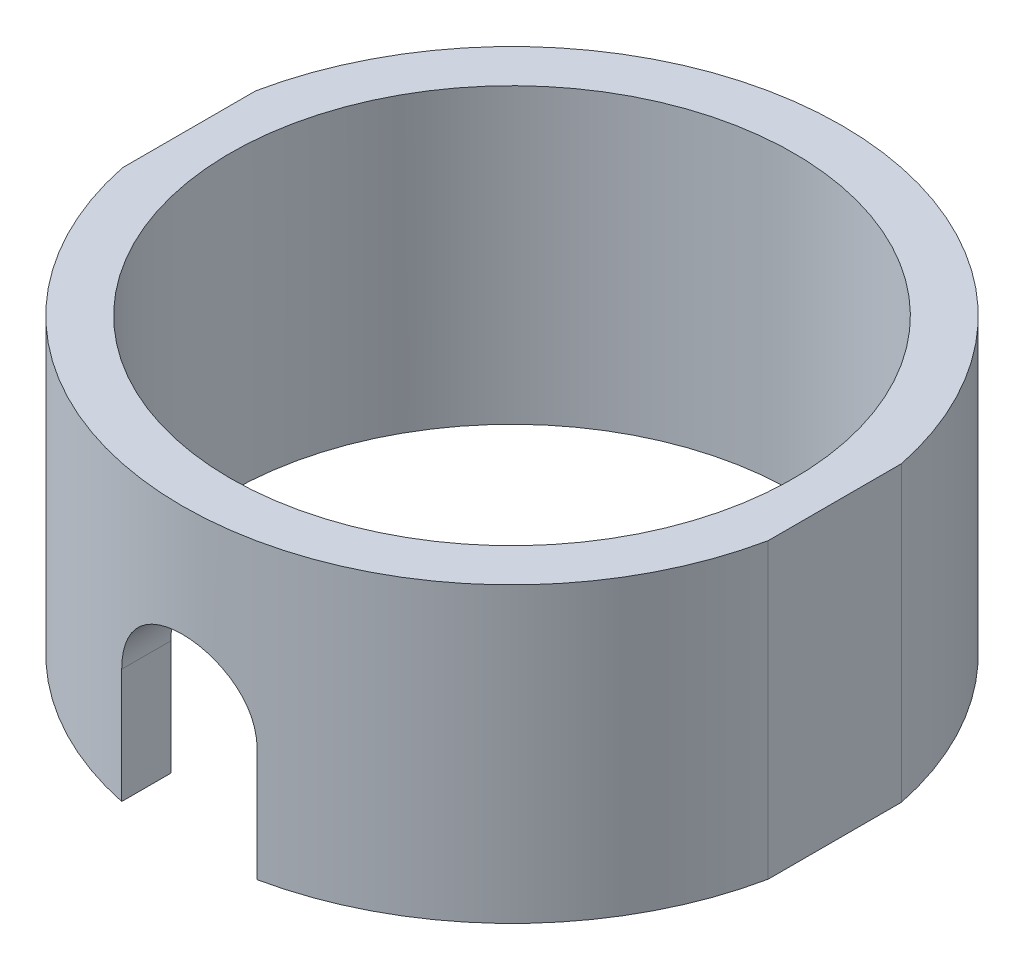
SolidWorks part; units mm, degrees
material "ABS"
ref_plane "Front Plane" through (0, 0, 0) normal (0, 0, 1) x (1, 0, 0)
ref_plane "Top Plane" through (0, 0, 0) normal (0, 1, 0) x (1, 0, 0)
ref_plane "Right Plane" through (0, 0, 0) normal (1, 0, 0) x (0, 0, -1)
sketch "Sketch1" plane through (0, 0, 0) normal (0, 1, 0) x (1, 0, 0)
  line L0 (-50.2186, 38.9495) -> (-51.24, 38.9495) construction
  line L1 (-50.2186, 13.9495) -> (-51.24, 13.9495) construction
  line L2 (-50.2186, 38.9495) -> (68.8614, 38.9495) construction
  line L3 (-50.2186, 13.9495) -> (68.8614, 13.9495) construction
  line L4 (68.8614, 38.9495) -> (69.8828, 38.9495) construction
  line L5 (68.8614, 13.9495) -> (69.8828, 13.9495) construction
  line L6 (-51.24, 38.9495) -> (-51.24, 13.9495)
  line L7 (69.8828, 38.9495) -> (69.8828, 13.9495)
  circle A0 centre (9.3214, 26.4495) radius 52.838
  arc A1 (-51.24, 13.9495) -> (69.8828, 13.9495) centre (9.3214, 26.4495) ccw
  arc A2 (69.8828, 38.9495) -> (-51.24, 38.9495) centre (9.3214, 26.4495) ccw
  dimension "D2" = 105.676
extrude "Boss-Extrude1" add sketch "Sketch1" along normal blind 54 and the other way blind 1
sketch "Sketch2" plane through (0, 0, 0) normal (0, 0, 1) x (1, 0, 0)
  line L2 (-3.3606, 20.5) -> (-3.3606, -1)
  line L4 (-3.3606, -1) -> (22.0034, -1)
  line L5 (22.0034, -1) -> (22.0034, 20.5)
  arc A0 (22.0034, 20.5) -> (-3.3606, 20.5) centre (9.3214, 20.5) ccw
  dimension "D1" = 12.682
extrude "Cut-Extrude1" cut sketch "Sketch2" along normal blind 53 contours A0
